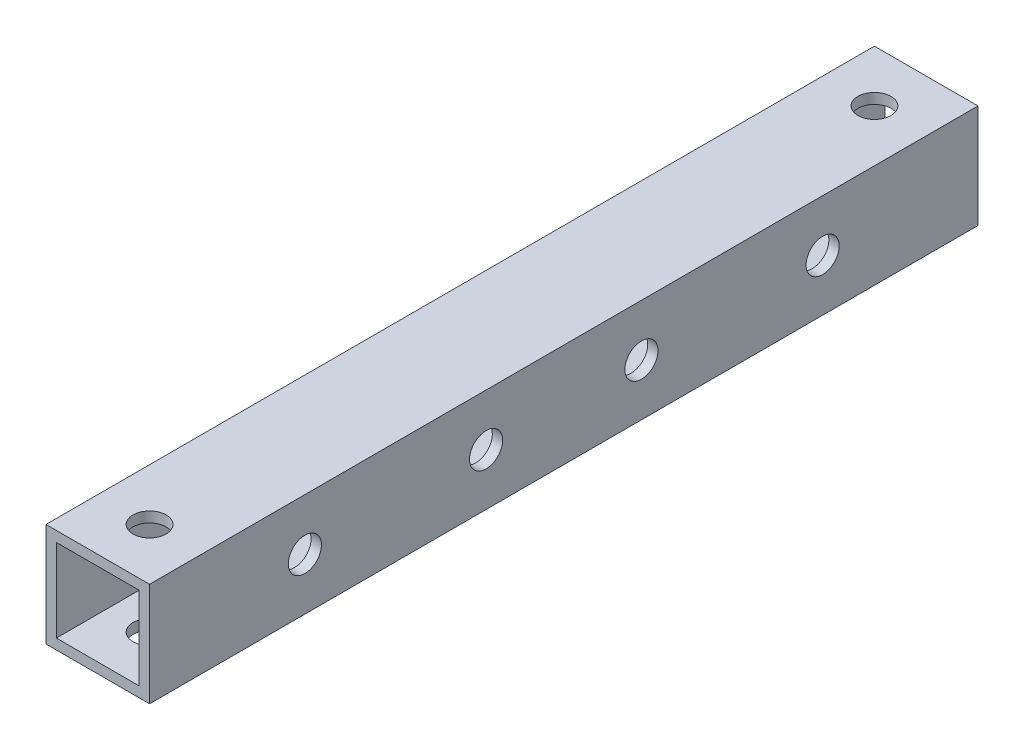
SolidWorks part; units mm, degrees
ref_plane "正面" through (0, 0, 0) normal (0, 0, 1) x (1, 0, 0)
ref_plane "平面" through (0, 0, 0) normal (0, 1, 0) x (1, 0, 0)
ref_plane "右側面" through (0, 0, 0) normal (1, 0, 0) x (0, 0, -1)
sketch "ｽｹｯﾁ1" plane through (0, 0, 0) normal (0, 0, 1) x (1, 0, 0)
  line L0 (-4, 4) -> (-4, -4)
  line L1 (-5, 5) -> (5, 5)
  line L2 (-5, 5) -> (-5, -5)
  line L3 (-5, -5) -> (5, -5)
  line L4 (5, 5) -> (5, -5)
  line L5 (-5, 5) -> (5, -5) construction
  line L6 (-5, -5) -> (5, 5) construction
  line L7 (-4, -4) -> (4, -4)
  line L8 (4, 4) -> (4, -4)
  line L9 (-4, 4) -> (4, 4)
  point P0 (0, 0)
  dimension "D1" = 10
  dimension "D2" = 10
  dimension "D3" = 1
extrude "ﾎﾞｽ - 押し出し1" add sketch "ｽｹｯﾁ1" along normal blind 80
sketch "ｽｹｯﾁ2" plane through (-5, 0, 0) normal (-1, 0, 0) x (0, 0, 1)
  line L0 (5.5, 0) -> (-5.5, 0) construction
  line L1 (0, -5.5) -> (0, 5.5) construction
  line L2 (80, 5) -> (80, -5) construction
  circle A0 centre (15, 0) radius 1.6
  circle A1 centre (65, 0) radius 1.6
  circle A2 centre (32.5, 0) radius 1.6
  circle A3 centre (47.5, 0) radius 1.6
  dimension "D1" = 3.2
  dimension "D2" = 3.2
  dimension "D5" = 3.2
  dimension "D6" = 3.2
  dimension "D3" = 15
  dimension "D4" = 15
  dimension "D7" = 15
  dimension "D8" = 32.5
extrude "ｶｯﾄ - 押し出し1" cut sketch "ｽｹｯﾁ2" against normal through all
sketch "ｽｹｯﾁ3" plane through (0, 5, 0) normal (0, 1, 0) x (1, 0, 0)
  line L0 (0, -5.5) -> (0, 5.5) construction
  line L1 (-5.5, 0) -> (5.5, 0) construction
  line L2 (5, -80) -> (-5, -80) construction
  circle A0 centre (0, -5) radius 1.6
  circle A1 centre (0, -75) radius 1.6
  dimension "D1" = 3.2
  dimension "D2" = 5
  dimension "D3" = 3.2
  dimension "D4" = 5
extrude "ｶｯﾄ - 押し出し2" cut sketch "ｽｹｯﾁ3" against normal through all
equation "\"D8@ｽｹｯﾁ2\"=(80-15)/2"
